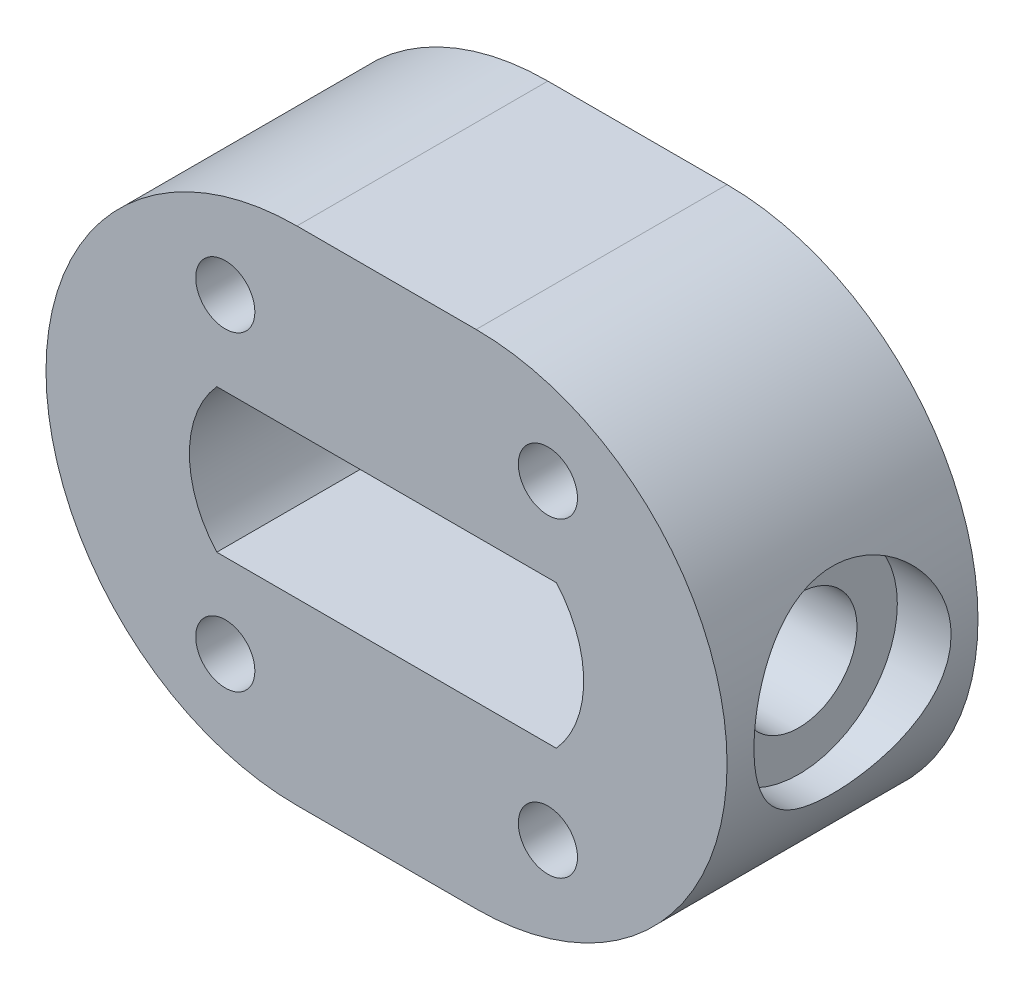
SolidWorks part; units mm, degrees
ref_plane "Front Plane" through (0, 0, 0) normal (0, 0, 1) x (1, 0, 0)
ref_plane "Top Plane" through (0, 0, 0) normal (0, 1, 0) x (1, 0, 0)
ref_plane "Right Plane" through (0, 0, 0) normal (1, 0, 0) x (0, 0, -1)
sketch "Sketch1" plane through (0, 0, 0) normal (0, 0, 1) x (1, 0, 0)
  line L0 (0, 0) -> (10, 0) construction
  line L1 (0, 14) -> (10, 14)
  line L2 (0, -14) -> (10, -14)
  line L3 (0, 0) -> (10, 0) construction
  line L6 (-4.4721, 4) -> (14.4721, 4)
  line L7 (-4.4721, -4) -> (14.4721, -4)
  arc A0 (0, 14) -> (0, -14) centre (0, 0) ccw
  arc A1 (10, -14) -> (10, 14) centre (10, 0) ccw
  arc A3 (-4.4721, 4) -> (-4.4721, -4) centre (0, 0) ccw
  arc A4 (14.4721, -4) -> (14.4721, 4) centre (10, 0) ccw
  point P3 (5, 0)
  point P12 (5, 0)
  dimension "D1" = 14
  dimension "D2" = 10
  dimension "D3" = 8
  dimension "D4" = 6
  dimension "D5" = 4
  dimension "D6" = 6
extrude "Boss-Extrude1" add sketch "Sketch1" along normal blind 14
sketch "Sketch2" plane through (0, 0, 14) normal (0, 0, 1) x (1, 0, 0)
  line L0 (0, 0) -> (10, 0) construction
  line L1 (5.0031, 0) -> (5.0031, 3.2311) construction
  circle A0 centre (5.0031, 0) radius 12.5 construction
  point P7 (-3.9969, 8.6747)
  point P11 (0, 0)
  point P12 (0, 0)
  point P13 (0, 0)
  point P14 (0, 0)
  point P15 (0, 0)
  point P16 (14.0031, 8.6747)
  point P17 (-3.9969, -8.6747)
  point P18 (14.0031, -8.6747)
  point P19 (0, 0)
  dimension "D1" = 25
  dimension "D2" = 8.6747
  dimension "D4" = 9
hole_wizard "M4 Tapped Hole2" positions "3DSketch2" profile "Sketch4" tap size "M4" standard "ISO" end condition through all
sketch3d "3DSketch2"
  point P0 (-3.9969, 8.6747, 14)
  point P3 (14.0031, 8.6747, 14)
  point P6 (14.0031, -8.6747, 14)
  point P9 (-3.9969, -8.6747, 14)
sketch "Sketch4" plane through (-3.9969, 8.6747, 14) normal (1, 0, 0) x (0, -1, 0)
  line L0 (0, 0) -> (0, 14)
  line L1 (0, 14) -> (1.65, 14)
  line L2 (1.65, 14) -> (1.65, 0)
  line L5 (1.65, 0) -> (0, 0)
  line L11 (0, -6.35) -> (0, 107.95) construction
  dimension "Thru Tap Drill Dia." = 3.3
  dimension "Thru Tap Drill Depth" = 14
cosmetic thread "Hole Thread5" parameters "D2"=4
cosmetic thread "Hole Thread6" parameters "D2"=4
cosmetic thread "Hole Thread7" parameters "D2"=4
cosmetic thread "Hole Thread8" parameters "D2"=4
ref_plane "Plane1" through (24, 0, 0) normal (1, 0, 0) x (0, 0, -1)
sketch "Sketch5" plane through (24, 0, 0) normal (1, 0, 0) x (0, 0, -1)
  line L0 (-14, 14) -> (0, 14) construction
  line L1 (0, -14) -> (0, 14) construction
  circle A0 centre (-7, 0) radius 3.25
  dimension "D1" = 6.5
  dimension "D2" = 14
  dimension "D3" = 7
extrude "Cut-Extrude1" cut sketch "Sketch5" against normal up to surface (8 mm away)
sketch "Sketch6" plane through (24, 0, 0) normal (1, 0, 0) x (0, 0, -1)
  circle A0 centre (-7, 0) radius 5.5
  dimension "D1" = 11
extrude "Cut-Extrude2" cut sketch "Sketch6" against normal blind 3
